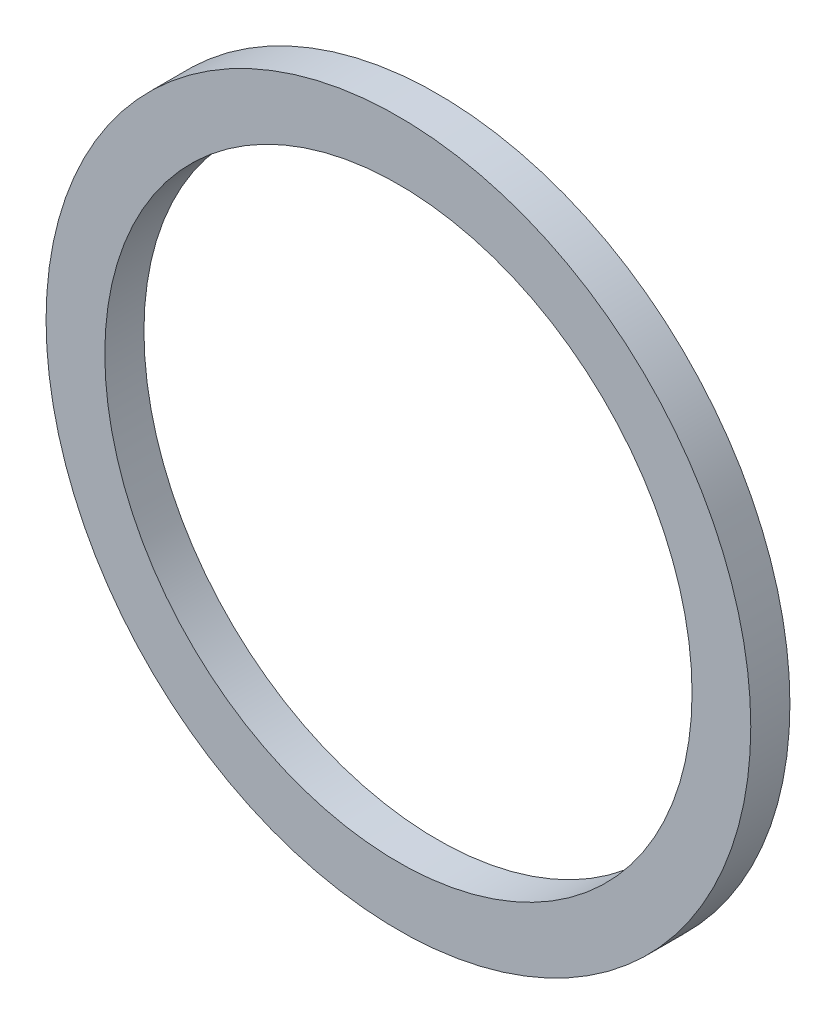
SolidWorks part; units mm, degrees
material "橡胶"
ref_plane "前视基准面" through (0, 0, 0) normal (0, 0, 1) x (1, 0, 0)
ref_plane "上视基准面" through (0, 0, 0) normal (0, 1, 0) x (1, 0, 0)
ref_plane "右视基准面" through (0, 0, 0) normal (1, 0, 0) x (0, 0, -1)
sketch "草图1" plane through (0, 0, 0) normal (0, 0, 1) x (1, 0, 0)
  circle A0 centre (0, 0) radius 1.8
  circle A1 centre (0, 0) radius 1.5
  dimension "D1" = 3.6
  dimension "D2" = 3
extrude "凸台-拉伸1" add sketch "草图1" along normal blind 0.2
